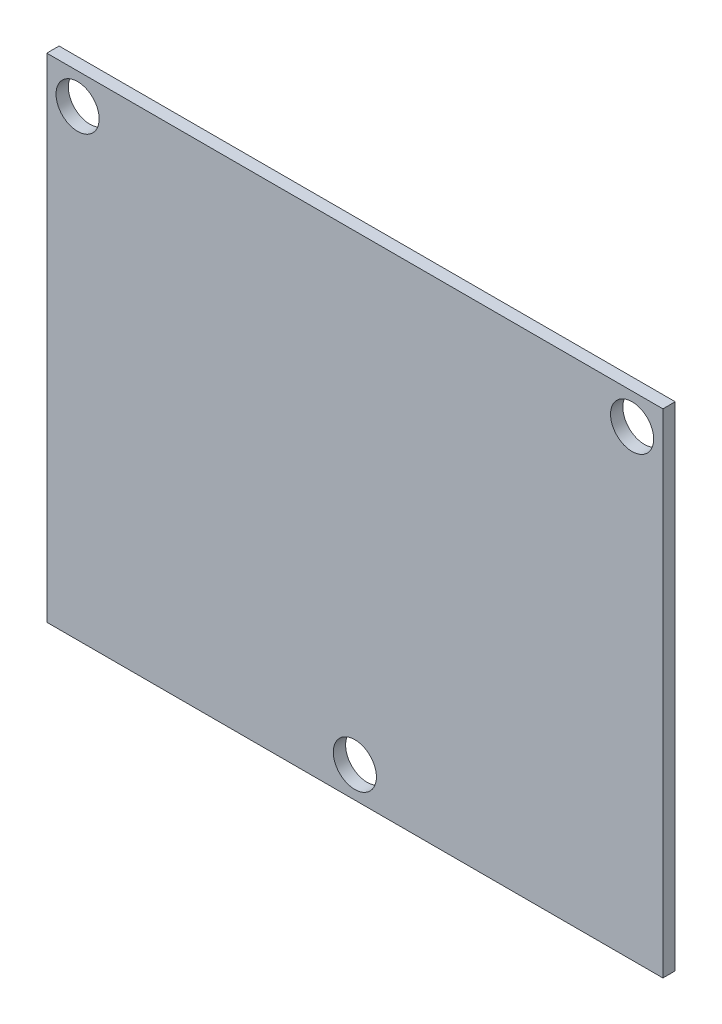
SolidWorks part; units mm, degrees
ref_plane "Front Plane" through (0, 0, 0) normal (0, 0, 1) x (1, 0, 0)
ref_plane "Top Plane" through (0, 0, 0) normal (0, 1, 0) x (1, 0, 0)
ref_plane "Right Plane" through (0, 0, 0) normal (1, 0, 0) x (0, 0, -1)
sketch "Sketch2" plane through (0, 0, 0) normal (0, 0, 1) x (1, 0, 0)
  line L1 (0, 0) -> (254, 0)
  line L2 (0, 0) -> (0, 203.2)
  line L3 (0, 203.2) -> (254, 203.2)
  line L4 (254, 0) -> (254, 203.2)
  dimension "D1" = 203.2
  dimension "D2" = 254
extrude "Boss-Extrude1" add sketch "Sketch2" along normal blind 5.08
sketch "Sketch3" plane through (0, 0, 5.08) normal (0, 0, 1) x (1, 0, 0)
  line L0 (254, 203.2) -> (0, 203.2) construction
  line L1 (0, 203.2) -> (0, 0) construction
  line L2 (254, 0) -> (254, 203.2) construction
  line L3 (0, 0) -> (254, 0) construction
  circle A0 centre (12.7, 190.5) radius 8.89
  circle A1 centre (241.3, 190.5) radius 8.89
  circle A2 centre (127, 12.7) radius 8.89
  dimension "D1" = 17.78
  dimension "D2" = 17.78
  dimension "D3" = 17.78
  dimension "D4" = 12.7
  dimension "D5" = 12.7
  dimension "D6" = 12.7
  dimension "D7" = 12.7
  dimension "D8" = 12.7
  dimension "D9" = 127
extrude "Cut-Extrude1" cut sketch "Sketch3" against normal through all
equation "\"FoamCore\" = \".2\""
equation "\"MDF\" = \".2\""
equation "\"GMaterial\"= \".2\""
equation "\"BaseWidth\" = \"10in\""
equation "\"BaseLength\" = \"8in\""
equation "\"D1@Sketch2\"=\"BaseLength\""
equation "\"D2@Sketch2\"=\"BaseWidth\""
equation "\"D1@Boss-Extrude1\"=\"GMaterial\""
equation "\"D1@Sketch3\"=\"PVCMountDiameter\" + \"PVCThickness\""
equation "\"D2@Sketch3\"=\"PVCMountDiameter\" + \"PVCThickness\""
equation "\"D3@Sketch3\"=\"PVCMountDiameter\" + \"PVCThickness\""
equation "\"D4@Sketch3\" = \"PVCMountDistanceToEdge\""
equation "\"D5@Sketch3\" = \"PVCMountDistanceToEdge\""
equation "\"D6@Sketch3\" = \"PVCMountDistanceToEdge\""
equation "\"D7@Sketch3\" = \"PVCMountDistanceToEdge\""
equation "\"D8@Sketch3\" = \"PVCMountDistanceToEdge\""
equation "\"D9@Sketch3\"=\"BaseWidth\" /2"
equation "\"PVCMountDiameter\" = \"0.5in\""
equation "\"PVCMountDistanceToEdge\" = \"0.5\""
equation "\"BallDiameter\" = \"1.57in\""
equation "\"BaseGap\" = \"4in\""
equation "\"FunnelTopDiameter\" = \"8in\""
equation "\"FunnelTopDepth\" = \"1.5in\""
equation "\"BallGap\" = \"0.1in\""
equation "\"FunnelLength\" = 6in"
equation "\"FunnelMaterial\" = 0.1in"
equation "\"FunnelLowerDiameter\" = \"BallDiameter\"+\"BallGap\""
equation "\"FunnelDepth\" = 1.5in"
equation "\"PVCThickness\" = \"0.2in\""
equation "\"AmmoFeederLength\" = 8in "
equation "\"AmmoFeederCutoffLength\" = 3in"
